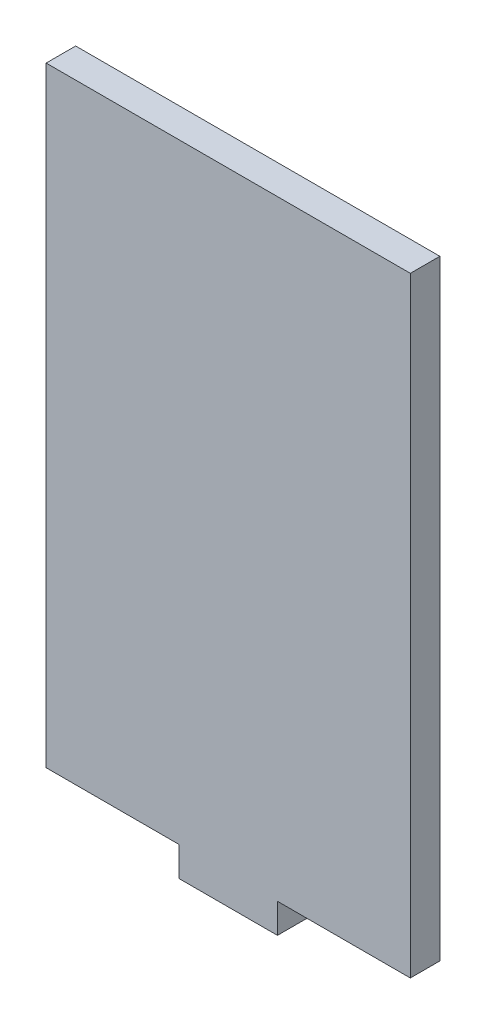
SolidWorks part; units mm, degrees
ref_plane "Plan de face" through (0, 0, 0) normal (0, 0, 1) x (1, 0, 0)
ref_plane "Plan de dessus" through (0, 0, 0) normal (0, 1, 0) x (1, 0, 0)
ref_plane "Plan de droite" through (0, 0, 0) normal (1, 0, 0) x (0, 0, -1)
sketch "Esquisse1" plane through (0, 0, 0) normal (0, 0, 1) x (1, 0, 0)
  line L0 (23.5, 0) -> (37, 0)
  line L1 (0, 0) -> (13.5, 0)
  line L2 (0, 0) -> (0, 62)
  line L3 (0, 62) -> (37, 62)
  line L4 (37, 0) -> (37, 62)
  line L15 (13.5, 0) -> (13.5, -3)
  line L16 (13.5, -3) -> (23.5, -3)
  line L17 (23.5, 0) -> (23.5, -3)
  dimension "D1" = 37
  dimension "D2" = 62
  dimension "D7" = 10
  dimension "D8" = 3
extrude "Boss.-Extru.1" add sketch "Esquisse1" along normal blind 3
